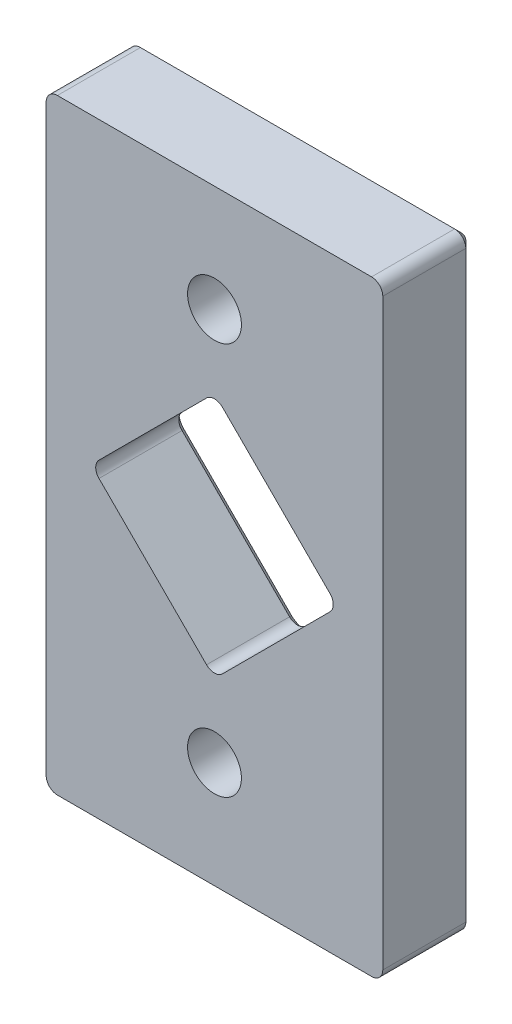
SolidWorks part; units mm, degrees
material "ABS"
ref_plane "Front Plane" through (0, 0, 0) normal (0, 0, 1) x (1, 0, 0)
ref_plane "Top Plane" through (0, 0, 0) normal (0, 1, 0) x (1, 0, 0)
ref_plane "Right Plane" through (0, 0, 0) normal (1, 0, 0) x (0, 0, -1)
sketch "Sketch1" plane through (0, 0, 0) normal (0, 0, 1) x (1, 0, 0)
  line L1 (15, -27) -> (-15, -27)
  line L2 (15, -27) -> (15, 27)
  line L3 (15, 27) -> (-15, 27)
  line L4 (-15, -27) -> (-15, 27)
  line L5 (15, -27) -> (-15, 27) construction
  line L6 (15, 27) -> (-15, -27) construction
  point P0 (0, 0)
  dimension "D1" = 30
  dimension "D2" = 54
extrude "Boss-Extrude1" add sketch "Sketch1" along normal blind 8
hole_wizard "M4 Clearance Hole1" positions "Sketch2" profile "Sketch3" hole size "M4" standard "DIN" end condition through all
sketch "Sketch2" plane through (0, 0, 8) normal (0, 0, 1) x (1, 0, 0)
  line L0 (-15, 0) -> (15, 0) construction
  line L1 (-15, 27) -> (-15, -27) construction
  line L2 (15, -27) -> (15, 27) construction
  line L4 (0, 0) -> (0, 17.5) construction
  point P0 (0, 17.5)
  point P2 (0, -17.5)
  point P18 (0, 12.5769)
  dimension "D1" = 35
sketch "Sketch3" plane through (0, 17.5, 8) normal (1, 0, 0) x (0, -1, 0)
  line L0 (0, 0) -> (0, 8)
  line L1 (0, 8) -> (2.4, 8)
  line L2 (2.4, 8) -> (2.4, 0)
  line L5 (2.4, 0) -> (0, 0)
  line L11 (0, -6.35) -> (0, 107.95) construction
  dimension "Thru Hole Dia." = 4.8
  dimension "Thru Hole Depth" = 8
sketch "Sketch4" plane through (0, 0, 8) normal (0, 0, 1) x (1, 0, 0)
  line L0 (11, 0) -> (0, 11)
  line L1 (11, 0) -> (0, -11)
  line L2 (0, 11) -> (-11, 0)
  line L3 (0, -11) -> (-11, 0)
  line L4 (11, 0) -> (-11, 0) construction
  line L5 (0, 11) -> (0, -11) construction
  line L6 (0, 17.5) -> (0, -17.5) construction
  point P1 (0, 0)
  point P3 (0, 12.6492)
  point P11 (11, 0)
  point P12 (0, 0)
  point P13 (0, -17.5)
  point P15 (0, 0)
  point P16 (0, 17.5)
  dimension "D1" = 22
extrude "Cut-Extrude1" cut sketch "Sketch4" against normal up to next
fillet "Fillet1" radius 1 8 edges at (15, -27, 4) (-15, -27, 4) (15, 27, 4) (-15, 27, 4) (0, -11, 4) (11, 0, 4) (0, 11, 4) (-11, 0, 4)
chamfer "Chamfer1" distance 0.6 angle 45 18 edges at (14.7071, 26.7071, 0) (0, 27, 0) (-14.7071, 26.7071, 0) (-15, 0, 0) (-14.7071, -26.7071, 0) (0, -27, 0) (14.7071, -26.7071, 0) (15, 0, 0) (-10.5858, 0, 0) (-5.5, 5.5, 0) (0, 10.5858, 0) (5.5, 5.5, 0) (10.5858, 0, 0) (5.5, -5.5, 0) (0, -10.5858, 0) (-5.5, -5.5, 0) (2.4, -17.5, 0) (2.4, 17.5, 0)
